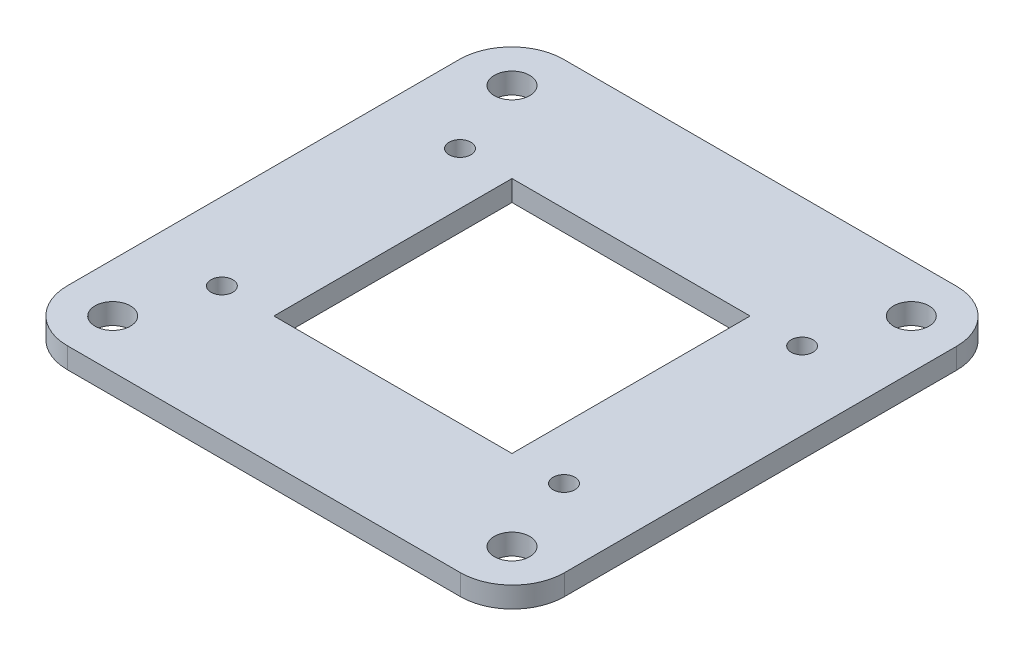
SolidWorks part; units mm, degrees
ref_plane "前视基准面" through (0, 0, 0) normal (0, 0, 1) x (1, 0, 0)
ref_plane "上视基准面" through (0, 0, 0) normal (0, 1, 0) x (1, 0, 0)
ref_plane "右视基准面" through (0, 0, 0) normal (1, 0, 0) x (0, 0, -1)
other "Configuration Table"
sketch "草图1" plane through (0, 0, 0) normal (0, 1, 0) x (1, 0, 0)
  line L0 (0, 19.2) -> (0, -25.11) construction
  line L5 (-19.2, 19.2) -> (19.2, -19.2) construction
  line L6 (-19.2, -19.2) -> (19.2, 19.2) construction
  line L7 (-19.2, 0) -> (51.0086, 0) construction
  line L8 (0, 19.2) -> (0, 20.4461) construction
  line L9 (-19.2, 0) -> (-19.5373, 0) construction
  line L10 (-19.2, 0) -> (-35.8239, 0) construction
  line L11 (-18.9, -23.8567) -> (18.9, -23.8567)
  line L12 (-23.9, -0.0433) -> (-23.9, 18.8567)
  line L13 (-18.9, 23.8567) -> (18.9, 23.8567)
  line L14 (0, 20.4461) -> (0, 29.225) construction
  line L15 (-23.9, 0.0433) -> (-23.9, -18.8567)
  line L16 (23.9, 0.0433) -> (23.9, -18.8567)
  line L17 (23.9, -0.0433) -> (23.9, 18.8567)
  line L23 (-16.45, 11.45) -> (16.45, -11.45) construction
  line L24 (-16.45, -11.45) -> (16.45, 11.45) construction
  line L25 (-11.45, -11.45) -> (11.45, -11.45)
  line L26 (-11.45, -11.45) -> (-11.45, 11.45)
  line L27 (-11.45, 11.45) -> (11.45, 11.45)
  line L28 (11.45, -11.45) -> (11.45, 11.45)
  line L29 (-11.45, -11.45) -> (11.45, 11.45) construction
  line L30 (-11.45, 11.45) -> (11.45, -11.45) construction
  circle A0 centre (-19.2, 19.2) radius 1.7
  circle A1 centre (-19.2, -19.2) radius 1.7
  circle A2 centre (19.2, -19.2) radius 1.7
  circle A3 centre (19.2, 19.2) radius 1.7
  circle A4 centre (-16.45, 11.45) radius 1.05
  circle A5 centre (-16.45, -11.45) radius 1.05
  circle A6 centre (16.45, -11.45) radius 1.05
  circle A7 centre (16.45, 11.45) radius 1.05
  arc A8 (-18.9, -23.8567) -> (-23.9, -18.8567) centre (-18.9, -18.8567) cw
  arc A9 (18.9, -23.8567) -> (23.9, -18.8567) centre (18.9, -18.8567) ccw
  arc A10 (23.9, 18.8567) -> (18.9, 23.8567) centre (18.9, 18.8567) ccw
  arc A11 (-18.9, 23.8567) -> (-23.9, 18.8567) centre (-18.9, 18.8567) ccw
  point P0 (0, 0)
  point P19 (0, 23.8567)
  point P25 (0, 23.8567)
  point P28 (0, 0)
  point P39 (-23.9, -23.8567)
  point P42 (23.9, -23.8567)
  point P45 (23.9, 23.8567)
  point P48 (-23.9, 23.8567)
  point P49 (0, 0)
  dimension "D3" = 23.9
  dimension "D7" = 5
  dimension "D1" = 38.4
  dimension "D2" = 38.4
  dimension "D4" = 23.9
  dimension "D5" = 32.9
  dimension "D6" = 22.9
extrude "凸台-拉伸1" add sketch "草图1" along normal blind 2 contours L16 L17 L13 L12 L15 L11 A5 A4 A1 A0 A2 A3 A6 A7
